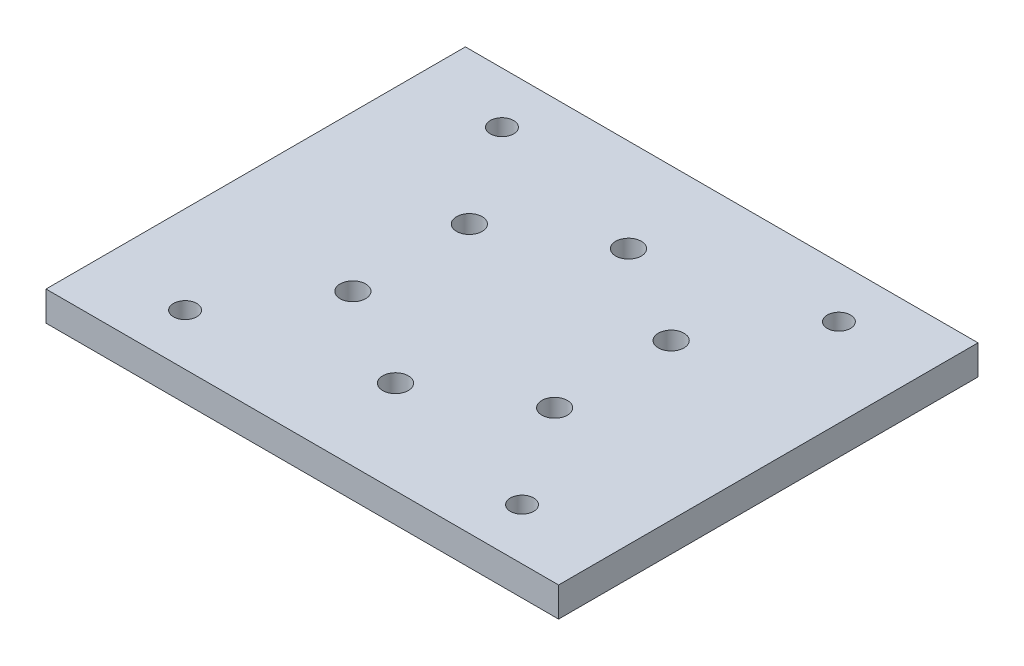
SolidWorks part; units mm, degrees
material "6061 Alloy"
ref_plane "Front Plane" through (0, 0, 0) normal (0, 0, 1) x (1, 0, 0)
ref_plane "Top Plane" through (0, 0, 0) normal (0, 1, 0) x (1, 0, 0)
ref_plane "Right Plane" through (0, 0, 0) normal (1, 0, 0) x (0, 0, -1)
sketch "Sketch2" plane through (0, 0, 0) normal (0, 1, 0) x (1, 0, 0)
  line L0 (0, 0) -> (0, 90)
  line L1 (0, 90) -> (110, 90)
  line L2 (110, 90) -> (110, 0)
  line L3 (110, 0) -> (0, 0)
  dimension "D1" = 110
  dimension "D2" = 90
extrude "Boss-Extrude1" add sketch "Sketch2" along normal blind 6.35
sketch "Sketch3" plane through (0, 6.35, 0) normal (0, 1, 0) x (1, 0, 0)
  line L1 (110, 90) -> (0, 90) construction
  line L2 (0, 0) -> (110, 0) construction
  line L4 (55, 90) -> (55, 0) construction
  line L5 (0, 45) -> (55, 45) construction
  line L6 (55, 45) -> (110, 45) construction
  line L7 (0, 90) -> (0, 0) construction
  circle A0 centre (18.85, 79) radius 2.5
  circle A1 centre (18.85, 11) radius 2.5
  circle A2 centre (91.15, 11) radius 2.5
  circle A3 centre (91.15, 79) radius 2.5
  dimension "D4" = 5
  dimension "D3" = 11
  dimension "D2" = 18.85
extrude "Mounting Holes" cut sketch "Sketch3" against normal through all
sketch "Sketch4" plane through (0, 6.35, 0) normal (0, 1, 0) x (1, 0, 0)
  line L0 (18.85, 79) -> (91.15, 11) construction
  circle A0 centre (55, 45) radius 25 construction
  circle A1 centre (55, 70) radius 2.75
  circle A2 centre (76.6506, 57.5) radius 2.75
  circle A3 centre (76.6506, 32.5) radius 2.75
  circle A4 centre (55, 20) radius 2.75
  circle A5 centre (33.3494, 32.5) radius 2.75
  circle A6 centre (33.3494, 57.5) radius 2.75
  point P20 (55, 45)
  dimension "D1" = 50
  dimension "D2" = 5.5
  dimension "D3" = 6
extrude "Cut-Extrude1" cut sketch "Sketch4" against normal through all
sketch "Sketch5" plane through (0, 6.35, 0) normal (0, 1, 0) x (1, 0, 0)
  circle A0 centre (55, 45) radius 25 construction
  circle A1 centre (55, 20) radius 2.75 construction
  circle A2 centre (55, 20) radius 2.75 construction
  circle A3 centre (33.3494, 32.5) radius 2.75 construction
  circle A4 centre (33.3494, 32.5) radius 2.75 construction
  circle A5 centre (33.3494, 57.5) radius 2.75 construction
  circle A6 centre (33.3494, 57.5) radius 2.75 construction
ref_plane "Plane1" through (55, 0, 0) normal (-1, 0, 0) x (0, 0, 1)
equation "\"L1L\"=500"
equation "\"L1Thick\"=6.35"
equation "\"Harm-Drive-Outer\"=74.5"
equation "\"L1-Spacing\"=100"
equation "\"L-Bracket-HoleToWall\"=12.5"
equation "\"D3@Sketch3\"=\"L-Bracket-HoleToSide\""
equation "\"L-Bracket-HoleToSide\"=11"
equation "\"Bracket-Hole-D\"=6.8"
equation "\"L1-Spacing\"=115.65"
equation "\"D2@Sketch3\"=\"L-Bracket-HoleToWall\"+\"L1Thick\""
